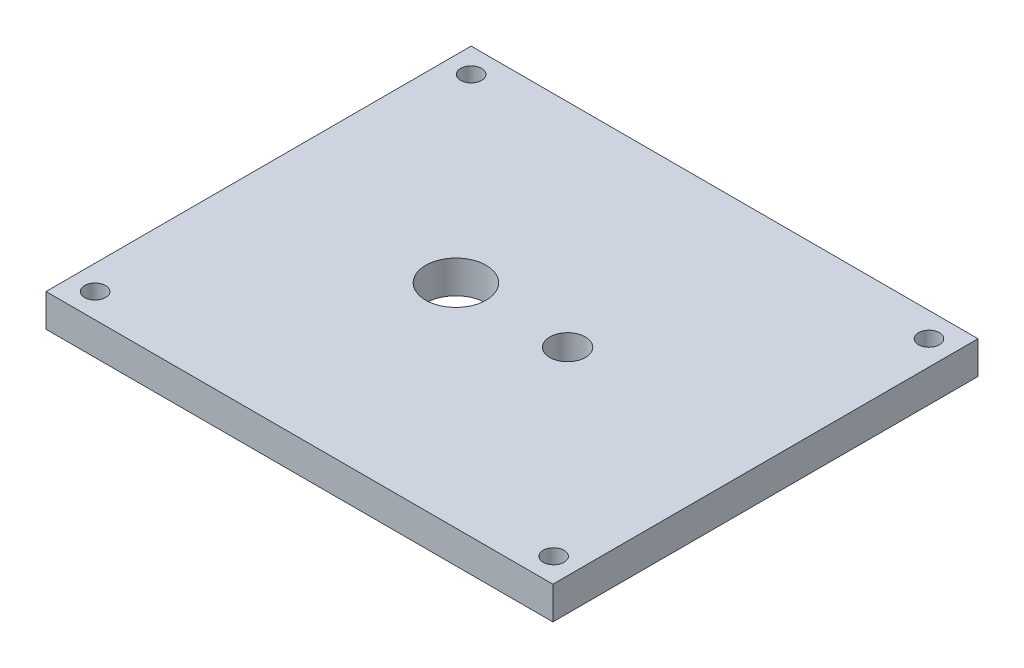
SolidWorks part; units mm, degrees
ref_plane "Front Plane" through (0, 0, 0) normal (0, 0, 1) x (1, 0, 0)
ref_plane "Top Plane" through (0, 0, 0) normal (0, 1, 0) x (1, 0, 0)
ref_plane "Right Plane" through (0, 0, 0) normal (1, 0, 0) x (0, 0, -1)
sketch "Sketch1" plane through (0, 0, 0) normal (0, 1, 0) x (1, 0, 0)
  line L1 (-39.37, -33.02) -> (39.37, -33.02)
  line L2 (-39.37, -33.02) -> (-39.37, 33.02)
  line L3 (-39.37, 33.02) -> (39.37, 33.02)
  line L4 (39.37, -33.02) -> (39.37, 33.02)
  line L5 (-39.37, -33.02) -> (39.37, 33.02) construction
  line L6 (-39.37, 33.02) -> (39.37, -33.02) construction
  point P0 (0, 0)
  dimension "D1" = 78.74
  dimension "D2" = 66.04
extrude "Boss-Extrude1" add sketch "Sketch1" along normal blind 5.08
sketch "Sketch2" plane through (0, 5.08, 0) normal (0, 1, 0) x (1, 0, 0)
  circle A0 centre (-8.7122, 0) radius 4.699
  circle A1 centre (8.636, 0) radius 2.7686
  dimension "D3" = 9.398
  dimension "D4" = 5.5372
  dimension "D1" = 8.7122
  dimension "D2" = 8.636
extrude "Cut-Extrude1" cut sketch "Sketch2" against normal blind 5.08
hole_wizard "#4 Clearance Hole1" positions "Sketch3" profile "Sketch4" hole size "#4" standard "ANSI Inch" end condition through all
sketch "Sketch3" plane through (0, 5.08, 0) normal (0, 1, 0) x (1, 0, 0)
  line L0 (39.37, 33.02) -> (-39.37, 33.02) construction
  line L1 (-39.37, 33.02) -> (-39.37, -33.02) construction
  line L2 (-39.37, -33.02) -> (39.37, -33.02) construction
  line L3 (39.37, -33.02) -> (39.37, 33.02) construction
  point P0 (-35.56, 29.21)
  point P2 (-35.56, -29.21)
  point P4 (35.6766, -29.21)
  point P6 (35.56, 29.21)
  point P17 (0, 0)
  dimension "D1" = 3.81
  dimension "D2" = 3.81
  dimension "D3" = 3.81
  dimension "D4" = 3.81
  dimension "D5" = 3.6934
  dimension "D6" = 3.81
  dimension "D7" = 3.81
  dimension "D8" = 3.81
sketch "Sketch4" plane through (-35.56, 5.08, -29.21) normal (1, 0, 0) x (0, 0, 1)
  line L0 (0, 0) -> (0, 5.08)
  line L1 (0, 5.08) -> (1.6256, 5.08)
  line L2 (1.6256, 5.08) -> (1.6256, 0)
  line L5 (1.6256, 0) -> (0, 0)
  line L11 (0, -6.35) -> (0, 107.95) construction
  dimension "Thru Hole Dia." = 3.2512
  dimension "Thru Hole Depth" = 5.08
